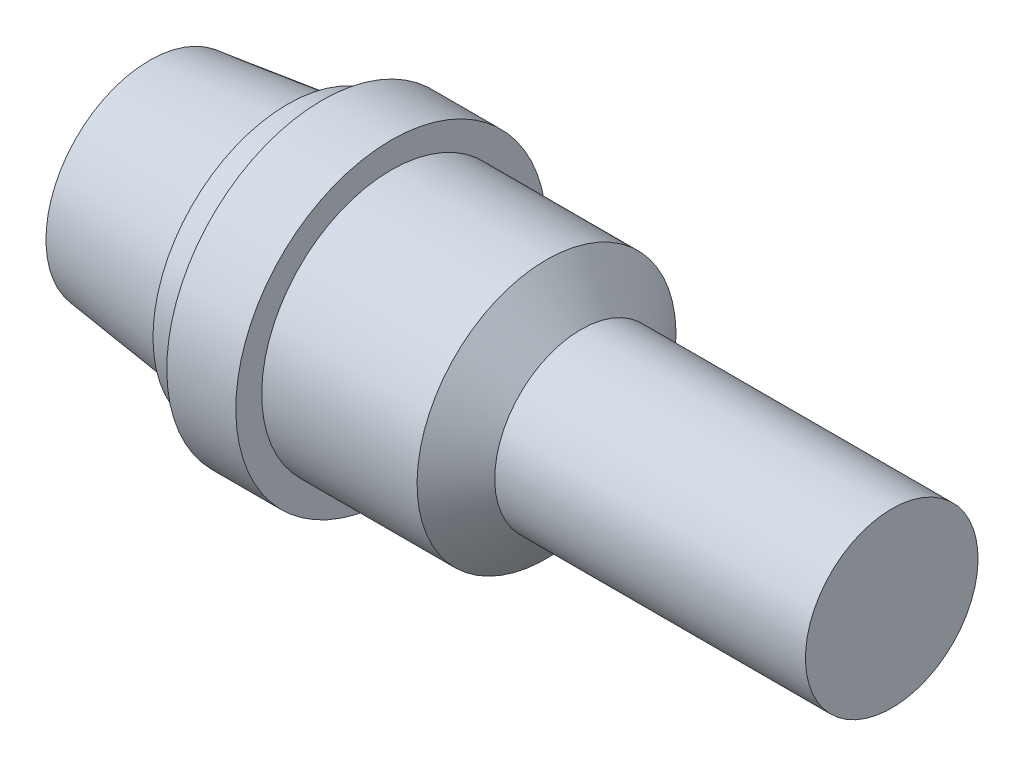
SolidWorks part; units mm, degrees
ref_plane "Plan de face" through (0, 0, 0) normal (0, 0, 1) x (1, 0, 0)
ref_plane "Plan de dessus" through (0, 0, 0) normal (0, 1, 0) x (1, 0, 0)
ref_plane "Plan de droite" through (0, 0, 0) normal (1, 0, 0) x (0, 0, -1)
sketch "Esquisse1" plane through (0, 0, 0) normal (0, 0, 1) x (1, 0, 0)
  line L0 (0, 0) -> (0, 6)
  line L1 (0, 6) -> (8, 7)
  line L2 (8, 7.8) -> (10, 7.8)
  line L3 (10, 7.8) -> (10, 9)
  line L4 (10, 9) -> (14, 9)
  line L5 (14, 9) -> (14, 7.5)
  line L6 (14, 7.5) -> (23, 7.5)
  line L7 (23, 7.5) -> (25, 5)
  line L8 (25, 5) -> (43, 5)
  line L9 (43, 5) -> (43, 0)
  line L10 (43, 0) -> (0, 0)
  line L11 (8, 7) -> (8, 7.8)
  dimension "D1" = 6
  dimension "D2" = 8
  dimension "D3" = 7
  dimension "D4" = 7.8
  dimension "D5" = 2
  dimension "D6" = 4
  dimension "D7" = 9
  dimension "D8" = 9
  dimension "D9" = 7.5
  dimension "D10" = 2
  dimension "D11" = 5
  dimension "D12" = 18
revolve "Révolution1" add sketch "Esquisse1" angle 360 about L10
sketch "Esquisse2" plane through (0, 0, 0) normal (-1, 0, 0) x (0, 0, 1)
  text T0 "<b>FUSE</b>"
extrude "Enlèv. mat.-Extru.1" cut sketch "Esquisse2" against normal blind 0.5
